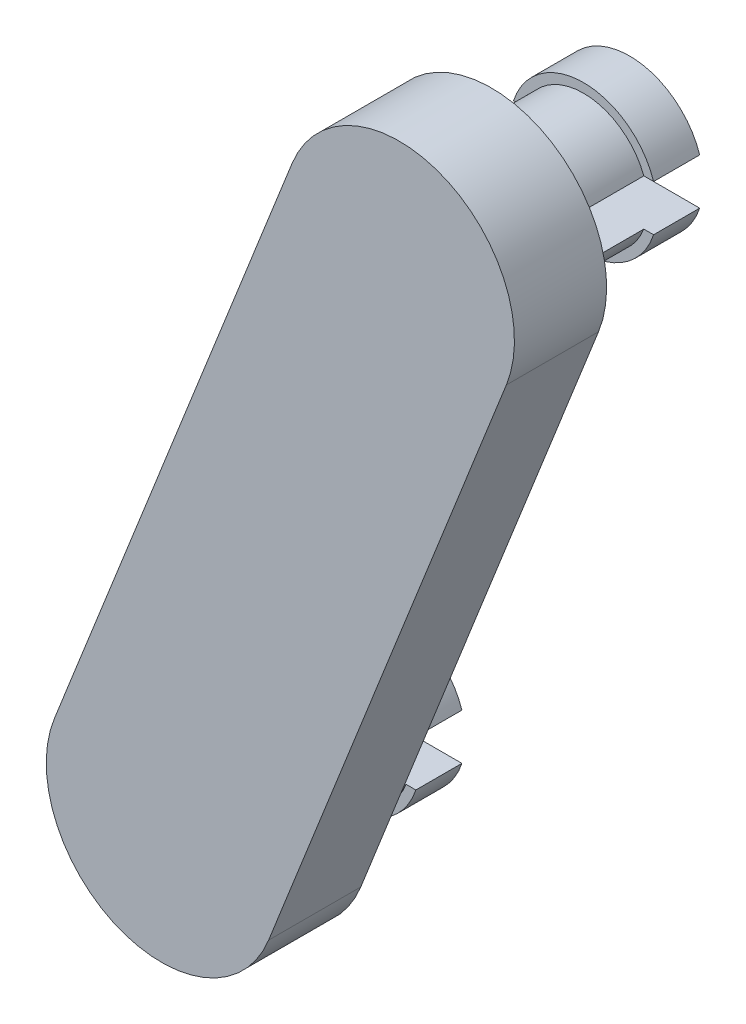
SolidWorks part; units mm, degrees
ref_plane "Plan de face" through (0, 0, 0) normal (0, 0, 1) x (1, 0, 0)
ref_plane "Plan de dessus" through (0, 0, 0) normal (0, 1, 0) x (1, 0, 0)
ref_plane "Plan de droite" through (0, 0, 0) normal (1, 0, 0) x (0, 0, -1)
sketch "Esquisse1" plane through (0, 0, 0) normal (0, 0, 1) x (1, 0, 0)
  line L0 (-29.4175, 2.9965) -> (-34.5773, -10.018) construction
  line L1 (-27.0935, 2.0751) -> (-32.2533, -10.9394)
  line L2 (-31.7415, 3.9179) -> (-36.9013, -9.0966)
  arc A0 (-27.0935, 2.0751) -> (-31.7415, 3.9179) centre (-29.4175, 2.9965) ccw
  arc A1 (-36.9013, -9.0966) -> (-32.2533, -10.9394) centre (-34.5773, -10.018) ccw
  point P4 (-31.9974, -3.5108)
  dimension "D1" = 5
extrude "Boss.-Extru.1" add sketch "Esquisse1" along normal blind 2
sketch "Esquisse2" plane through (0, 0, 0) normal (0, 0, -1) x (-1, 0, 0)
  circle A0 centre (29.4175, 2.9965) radius 1.4
  circle A1 centre (34.5773, -10.018) radius 1.4
  dimension "D1" = 2.8
  dimension "D2" = 2.8
extrude "Boss.-Extru.2" add sketch "Esquisse2" along normal blind 2 contours A0 | A1
sketch "Esquisse3" plane through (0, 0, -2) normal (0, 0, -1) x (-1, 0, 0)
  circle A0 centre (34.5773, -10.018) radius 1.6
  circle A1 centre (29.4175, 2.9965) radius 1.6
  dimension "D1" = 3.2
  dimension "D2" = 3.2
extrude "Boss.-Extru.3" add sketch "Esquisse3" along normal blind 1 contours A1 | A0
sketch "Esquisse4" plane through (0, 0, -3) normal (0, 0, -1) x (-1, 0, 0)
  line L1 (27.4175, 3.4965) -> (31.4175, 3.4965)
  line L2 (27.4175, 3.4965) -> (27.4175, 2.4965)
  line L3 (27.4175, 2.4965) -> (31.4175, 2.4965)
  line L4 (31.4175, 3.4965) -> (31.4175, 2.4965)
  line L5 (32.5773, -9.518) -> (36.5773, -9.518)
  line L6 (32.5773, -9.518) -> (32.5773, -10.518)
  line L7 (32.5773, -10.518) -> (36.5773, -10.518)
  line L8 (36.5773, -9.518) -> (36.5773, -10.518)
  dimension "D1" = 0.5
  dimension "D2" = 1
  dimension "D3" = 0.5
  dimension "D4" = 1
  dimension "D5" = 2
  dimension "D6" = 2
  dimension "D7" = 4
  dimension "D8" = 4
extrude "Enlèv. mat.-Extru.1" cut sketch "Esquisse4" against normal blind 3 contours L6 L5 L8 L7 | L2 L1 L4 L3
